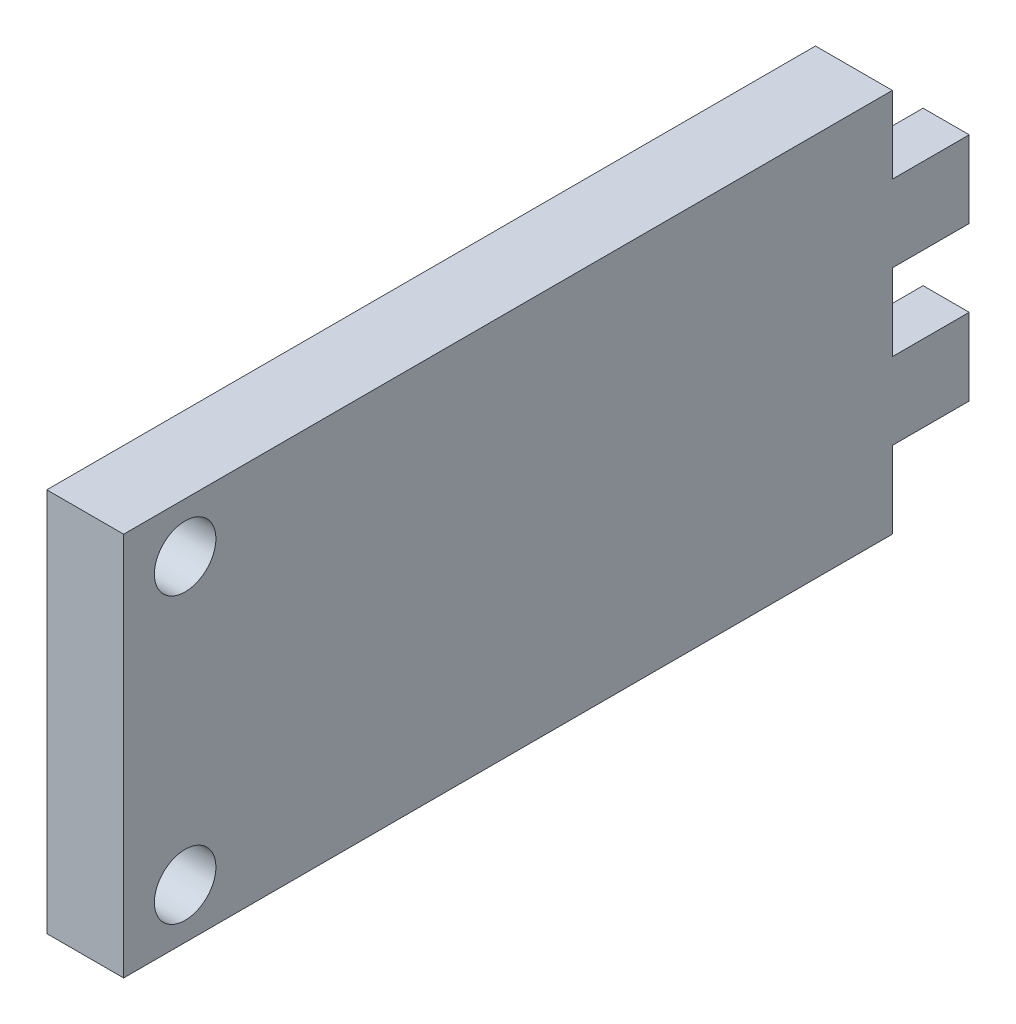
SolidWorks part; units mm, degrees
ref_plane "Front Plane" through (0, 0, 0) normal (0, 0, 1) x (1, 0, 0)
ref_plane "Top Plane" through (0, 0, 0) normal (0, 1, 0) x (1, 0, 0)
ref_plane "Right Plane" through (0, 0, 0) normal (1, 0, 0) x (0, 0, -1)
sketch "Sketch1" plane through (0, 0, 0) normal (0, 0, 1) x (1, 0, 0)
  line L0 (11.157, -14.3595) -> (-13.843, -14.3595) construction
  line L1 (11.157, 10.6405) -> (6.157, 10.6405)
  line L2 (11.157, 10.6405) -> (11.157, -14.3595)
  line L3 (11.157, -14.3595) -> (6.157, -14.3595)
  line L4 (6.157, 10.6405) -> (6.157, -14.3595)
  dimension "D1" = 5
extrude "Boss-Extrude1" add sketch "Sketch1" along normal blind 50
sketch "Sketch2" plane through (6.157, 0, 0) normal (-1, 0, 0) x (0, 0, 1)
  circle A1 centre (46, -11.1095) radius 2
  circle A2 centre (46, 7.3905) radius 2
  dimension "D1" = 4
  dimension "D2" = 4
extrude "Cut-Extrude1" cut sketch "Sketch2" against normal blind 15
sketch "Sketch3" plane through (0, 0, 0) normal (0, 0, -1) x (-1, 0, 0)
  line L0 (-11.157, -14.3595) -> (-11.157, 10.6405) construction
  line L1 (-11.157, 5.6391) -> (-8.157, 5.6391)
  line L2 (-11.157, 5.6391) -> (-11.157, 0.6405)
  line L3 (-11.157, 0.6405) -> (-8.157, 0.6405)
  line L4 (-8.157, 5.6391) -> (-8.157, 0.6405)
  line L6 (-8.157, -9.3595) -> (-11.157, -9.3595)
  line L7 (-8.157, -9.3595) -> (-8.157, -4.3595)
  line L8 (-8.157, -4.3595) -> (-11.157, -4.3595)
  line L9 (-11.157, -9.3595) -> (-11.157, -4.3595)
extrude "Boss-Extrude2" add sketch "Sketch3" along normal blind 5
